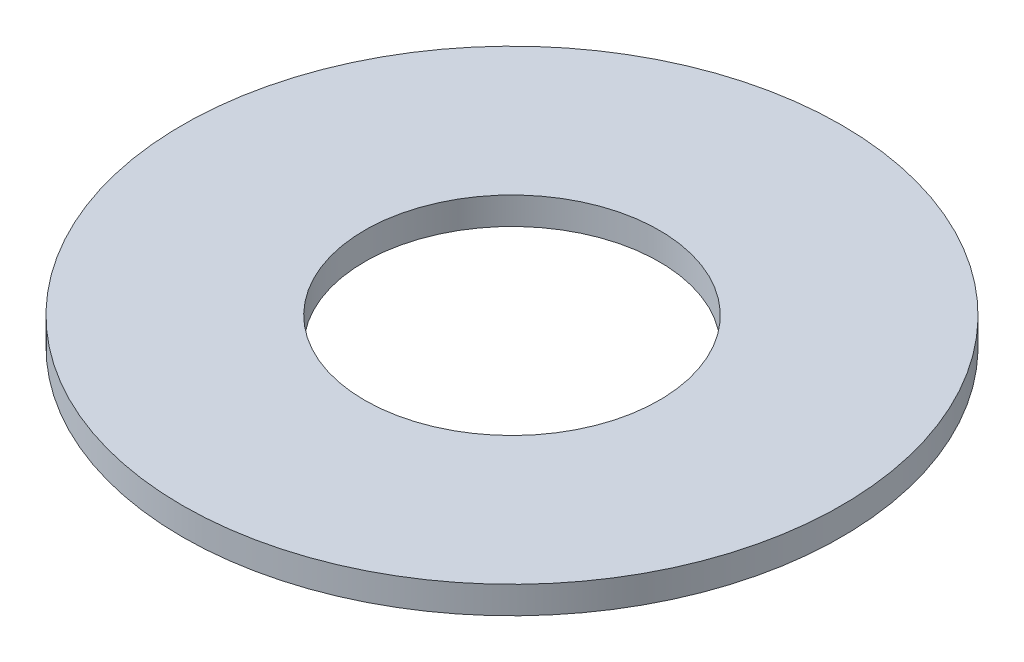
SolidWorks part; units mm, degrees
ref_plane "Front Plane" through (0, 0, 0) normal (0, 0, 1) x (1, 0, 0)
ref_plane "Top Plane" through (0, 0, 0) normal (0, 1, 0) x (1, 0, 0)
ref_plane "Right Plane" through (0, 0, 0) normal (1, 0, 0) x (0, 0, -1)
sketch "Sketch1" plane through (0, 0, 0) normal (0, 1, 0) x (1, 0, 0)
  circle A0 centre (0, 0) radius 24.15
  circle A1 centre (0, 0) radius 10.795
  dimension "D1" = 48.3
  dimension "D2" = 21.59
extrude "Boss-Extrude1" add sketch "Sketch1" along normal blind 2
